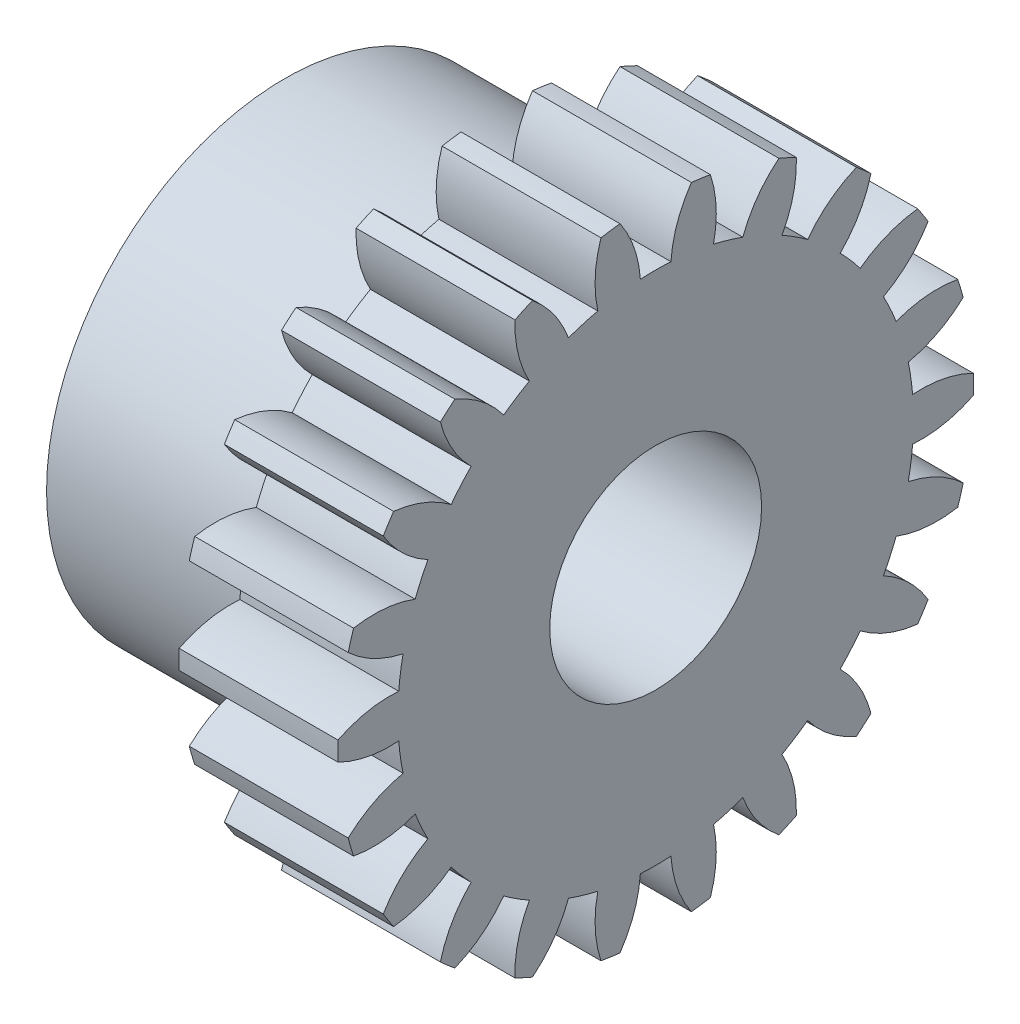
SolidWorks part; units mm, degrees
ref_plane "Plane1" through (0, 0, 0) normal (0, 0, 1) x (1, 0, 0)
ref_plane "Plane2" through (0, 0, 0) normal (0, 1, 0) x (1, 0, 0)
ref_plane "Plane3" through (0, 0, 0) normal (1, 0, 0) x (0, 0, -1)
sketch "HoldingSke" plane through (0, 0, 0) normal (0, 1, 0) x (1, 0, 0)
  line L0 (0, 0) -> (753.615, -304.4802)
  line L1 (-15, 0) -> (100, 0) construction
  line L2 (0, 0) -> (-2.1039, 2.3779)
  line L3 (0, 0) -> (-11.863, 4.5341)
  line L4 (0, 0) -> (8.0072, 3.2351)
  line L5 (0, 0) -> (-10.4119, -3.8833)
  line L6 (0, 0) -> (-3.9479, -2.6637)
  line L7 (-2.1039, 2.3779) -> (0.2881, 13.2299)
  line L8 (-76.2, 54.61) -> (-69.596, 54.61)
  line L9 (-67.7845, 28.3722) -> (-49.3413, 33.142)
  line L10 (-76.2, 71.12) -> (104.1128, 71.12)
  line L11 (0, 0) -> (-4.7625, 0)
  line L12 (-76.2, 101.6) -> (-76.1716, 101.6)
  line L13 (24.9733, 27.94) -> (52.9518, 28.4284)
  line L14 (24.9733, 27.94) -> (25.0241, 27.9398)
  line L15 (24.9733, 27.94) -> (100.4021, 29.52)
  circle A0 centre (0, 0) radius 3.175
  circle A1 centre (0, 0) radius 7.1438
  circle A2 centre (0, 0) radius 7.1438
  circle A3 centre (0, 0) radius 3.175
  dimension "MHD" = 14.2875
  dimension "Hub_dia" = 14.2875
  dimension "Bore" = 6.35
  dimension "MBD" = 6.35
  dimension "Num_teeth" = 22
  dimension "Pitch_radius" = 180.3128
  dimension "Pitch" = 812.8
  dimension "Width" = 4.7625
  dimension "Overall_len" = 11.1125
  dimension "Show_teeth" = 22
  dimension "Thickness" = 4.7625
  dimension "OAL" = 11.1126
  dimension "T_dim" = 6.604
  dimension "Ap" = 14.5
  dimension "H" = 19.05
  dimension "Backlash" = 0.0284
  dimension "Addendum_fac" = 1
  dimension "Dedendum_fac" = 1.2
  dimension "Clearance_fac" = 0.2
  dimension "Dedendum_add" = 0.0508
sketch "BasProSke" plane through (0, 0, 0) normal (0, 1, 0) x (1, 0, 0)
  line L0 (-10, 0) -> (60, 0) construction
  line L1 (0, 0) -> (0, 9.525)
  line L2 (0, 0) -> (4.7625, 0)
  line L3 (4.7625, 0) -> (4.7625, 9.525)
  line L4 (4.7625, 9.525) -> (0, 9.525)
  dimension "Diameter" = 19.05
  dimension "Thickness" = 4.7625
revolve "Base-Revolve" add sketch "BasProSke" angle 360 about L0
sketch "TooCutSke" plane through (0, 0, 0) normal (1, 0, 0) x (0, 0, -1)
  line L1 (0, 0) -> (0, 107) construction
  line L2 (0, 0) -> (-0.6726, 8.7053) construction
  line L3 (0, 0) -> (-2.4798, 17.2475) construction
  line L4 (-0.6726, 8.7053) -> (-1.2399, 8.6237) construction
  arc A0 (0.4578, 7.7144) -> (-0.4578, 7.7144) centre (0, 0) ccw
  arc A1 (1.0867, 9.4884) -> (-1.0867, 9.4884) centre (0, 0) ccw
  circle A2 centre (0, 0) radius 8.7312 construction
  circle A3 centre (0, 0) radius 8.4531 construction
  arc A4 (-0.4578, 7.7144) -> (-1.0867, 9.4884) centre (-3.9422, 7.4776) ccw
  arc A5 (1.0867, 9.4884) -> (0.4578, 7.7144) centre (3.9422, 7.4776) ccw
  dimension "Root_dia" = 15.4559
  dimension "Overcut_dia" = 19.1008
  dimension "Pitch_dia" = 17.4625
  dimension "Base_dia" = 16.9063
  dimension "Flank_rad" = 3.4925
  dimension "Half_ang" = 8.182
  dimension "Half_CT" = 0.5731
extrude "ToothCut" cut sketch "TooCutSke" along normal through all
fillet "Breaks" [suppressed] radius 0.0159
fillet "RootFillets" [suppressed] radius 0.2095
pattern_circular "TeethCuts" count 22 every 16.364 about axis through (-10, 0, 0) along (1, 0, 0) of "ToothCut", "RootFillets", "Breaks"
sketch "HubNeaOneSke" plane through (0, 0, 0) normal (-1, 0, 0) x (0, 0, 1)
  circle A0 centre (0, 0) radius 7.1438
  dimension "Diameter" = 14.2875
extrude "HubNearOne" add sketch "HubNeaOneSke" along normal blind 6.3501
sketch "HubNeaBotSke" plane through (0, 0, 0) normal (-1, 0, 0) x (0, 0, 1)
  circle A0 centre (0, 0) radius 7.1438
  dimension "Diameter" = 14.2875
extrude "HubNearBoth" [suppressed] add sketch "HubNeaBotSke" along normal blind 3.175
ref_plane "FarPln" through (4.7625, 0, 0) normal (1, 0, 0) x (0, 0, -1)
sketch "HubFarSke" plane through (4.7625, 0, 0) normal (1, 0, 0) x (0, 0, -1)
  circle A0 centre (0, 0) radius 7.1438
  dimension "Diameter" = 14.2875
extrude "HubFar" [suppressed] add sketch "HubFarSke" along normal blind 3.175
sketch "BorSke" plane through (0, 0, 0) normal (1, 0, 0) x (0, 0, -1)
  circle A0 centre (0, 0) radius 3.175
  dimension "Diameter" = 6.35
extrude "Bore" cut sketch "BorSke" along normal mid plane 22.2251
sketch "KeySke" plane through (0, 0, 0) normal (1, 0, 0) x (0, 0, -1)
  line L0 (-0.127, 0) -> (-0.127, 3.429)
  line L1 (-0.127, 3.429) -> (0.127, 3.429)
  line L2 (0.127, 3.429) -> (0.127, 0)
  line L3 (0, 0) -> (0, 34) construction
  line L4 (-0.127, 0) -> (0.127, 0)
  dimension "Offset" = 3.429
  dimension "Width" = 0.254
extrude "Keyway" [suppressed] cut sketch "KeySke" along normal mid plane 22.2251
pattern_circular "Keyway2" [suppressed] count 2 every 90 about axis through (-10, 0, 0) along (1, 0, 0)
equation "' \"Pitch@HoldingSke\" = 4"
equation "' \"Num_teeth@HoldingSke\" = 12"
equation "' \"Ap@HoldingSke\" =  20"
equation "' \"Width@HoldingSke\" = 0.5"
equation "' \"Hub_dia@HoldingSke\"= 1"
equation "' \"Overall_len@HoldingSke\" = 1.0"
equation "' \"Bore@HoldingSke\" = 0.75"
equation "' \"T_dim@HoldingSke\" = 0.85"
equation "' \"Width@KeySke\" = 0.25"
equation "' \"Show_teeth@HoldingSke\" = 13"
equation "' \"Backlash@HoldingSke\" = 0.009"
equation "' \"Addendum_fac@HoldingSke\" = 1.0"
equation "' \"Dedendum_fac@HoldingSke\" = 1.25"
equation "' \"Dedendum_add@HoldingSke\" = 0.00005"
equation "' \"Clearance_fac@HoldingSke\" = 0.25"
equation "' \"Pitch@HoldingSke\" = 0.5"
equation "' \"Num_teeth@HoldingSke\" = 23"
equation "' \"Show_teeth@HoldingSke\" = 23"
equation "' \"Backlash@HoldingSke\" = 0.0375"
equation "\"Overcut_dia@TooCutSke\" = (\"Num_teeth@HoldingSke\" + 2 * \"Addendum_fac@HoldingSke\") / \"Pitch@HoldingSke\" + 0.002"
equation "\"Pitch_dia@TooCutSke\" = \"Num_teeth@HoldingSke\" / \"Pitch@HoldingSke\""
equation "\"Base_dia@TooCutSke\" = \"Num_teeth@HoldingSke\" / \"Pitch@HoldingSke\" * cos((\"Ap@HoldingSke\"  * 3.14159265 / 180))"
equation "\"Root_dia@TooCutSke\" = (\"Num_teeth@HoldingSke\" + 2) / \"Pitch@HoldingSke\" - 2 * (\"Addendum_fac@HoldingSke\" + \"Dedendum_fac@HoldingSke\") / \"Pitch@HoldingSke\" - \"Dedendum_add@HoldingSke\" * 2"
equation "\"Half_ang@TooCutSke\" = 180 / \"Num_teeth@HoldingSke\""
equation "\"Half_CT@TooCutSke\" = \"Num_teeth@HoldingSke\" / \"Pitch@HoldingSke\" * sin((3.14159265 / 2 / \"Num_teeth@HoldingSke\")) / 2 - 7 * \"Backlash@HoldingSke\" / 4"
equation "\"Flank_rad@TooCutSke\" = \"Num_teeth@HoldingSke\" / \"Pitch@HoldingSke\" / 5"
equation "\"Radius@RootFillets\" = \"Clearance_fac@HoldingSke\" / \"Pitch@HoldingSke\" + \"Dedendum_add@HoldingSke\""
equation "\"Break_rad@Breaks\" = 0.02 / \"Pitch@HoldingSke\""
equation "\"Thickness@HoldingSke\" = \"Width@HoldingSke\""
equation "\"OAL@HoldingSke\" = \"Thickness@HoldingSke\""
equation "\"MHD@HoldingSke\" = (\"Num_teeth@HoldingSke\" + 2) / \"Pitch@HoldingSke\" - 2 * (\"Addendum_fac@HoldingSke\" + \"Dedendum_fac@HoldingSke\")  / \"Pitch@HoldingSke\" - \"Dedendum_add@HoldingSke\" * 2"
equation "\"MBD@HoldingSke\" = (\"Num_teeth@HoldingSke\" + 2) / \"Pitch@HoldingSke\" - 2 * (\"Addendum_fac@HoldingSke\" + \"Dedendum_fac@HoldingSke\")  / \"Pitch@HoldingSke\" - \"Dedendum_add@HoldingSke\" * 2 - 0.002"
equation "\"MHD@HoldingSke\" = ((sgn( \"MHD@HoldingSke\" - \"Hub_dia@HoldingSke\" )-1)*( \"MHD@HoldingSke\" - \"Hub_dia@HoldingSke\" ))/-2+ \"Hub_dia@HoldingSke\""
equation "\"MBD@HoldingSke\" = ((sgn( \"MBD@HoldingSke\" - \"Bore@HoldingSke\" )-1)*( \"MBD@HoldingSke\" - \"Bore@HoldingSke\" ))/-2+ \"Bore@HoldingSke\""
equation "\"OAL@HoldingSke\" = ((sgn( \"OAL@HoldingSke\" - \"Overall_len@HoldingSke\" )+1)*( \"OAL@HoldingSke\" - \"Overall_len@HoldingSke\" ))/2 + \"Overall_len@HoldingSke\" + 0.000002"
equation "\"Num_teeth@TeethCuts\" = int( \"Show_teeth@HoldingSke\" ) + 1"
equation "\"Num_teeth@TeethCuts\" = ((sgn( \"Num_teeth@TeethCuts\" - \"Num_teeth@HoldingSke\" )-1)*( \"Num_teeth@TeethCuts\" - \"Num_teeth@HoldingSke\" ))/-2+ \"Num_teeth@HoldingSke\""
equation "\"Num_teeth@TeethCuts\" = ((sgn( \"Num_teeth@TeethCuts\" - 2.0)+1)*( \"Num_teeth@TeethCuts\" - 2.0))/2 +2.0"
equation "\"Angle@TeethCuts\" = 360.0 / \"Num_teeth@HoldingSke\""
equation "\"Diameter@BasProSke\" = (\"Num_teeth@HoldingSke\" + 2 * \"Addendum_fac@HoldingSke\") / \"Pitch@HoldingSke\""
equation "\"Thickness@BasProSke\"  = \"Thickness@HoldingSke\""
equation "' \"Fillet_rad@BasProSke\" =  \"Thickness@HoldingSke\" * 0.05"
equation "\"MHD@HoldingSke\" = ((sgn( \"MHD@HoldingSke\" - \"Root_dia@TooCutSke\" )-1)*( \"MHD@HoldingSke\" - \"Root_dia@TooCutSke\" ))/-2+ \"Root_dia@TooCutSke\""
equation "\"Diameter@HubNeaOneSke\" = \"MHD@HoldingSke\""
equation "\"Length@HubNearOne\" = \"OAL@HoldingSke\" - \"Thickness@BasProSke\""
equation "\"Diameter@HubNeaBotSke\" = \"MHD@HoldingSke\""
equation "\"Length@HubNearBoth\" = ( \"OAL@HoldingSke\" - \"Thickness@BasProSke\" ) / 2.0"
equation "\"Thickness@FarPln\" = \"Thickness@BasProSke\""
equation "\"Diameter@HubFarSke\" = \"MHD@HoldingSke\""
equation "\"Length@HubFar\" = ( \"OAL@HoldingSke\" - \"Thickness@BasProSke\" ) / 2.0"
equation "\"Diameter@BorSke\" = \"MBD@HoldingSke\""
equation "\"D1@Bore\" = \"OAL@HoldingSke\" * 2.0"
equation "\"D1@Keyway\" = \"OAL@HoldingSke\" * 2.0"
equation "\"Offset@KeySke\" = \"T_dim@HoldingSke\" - \"MBD@HoldingSke\" / 2.0"
